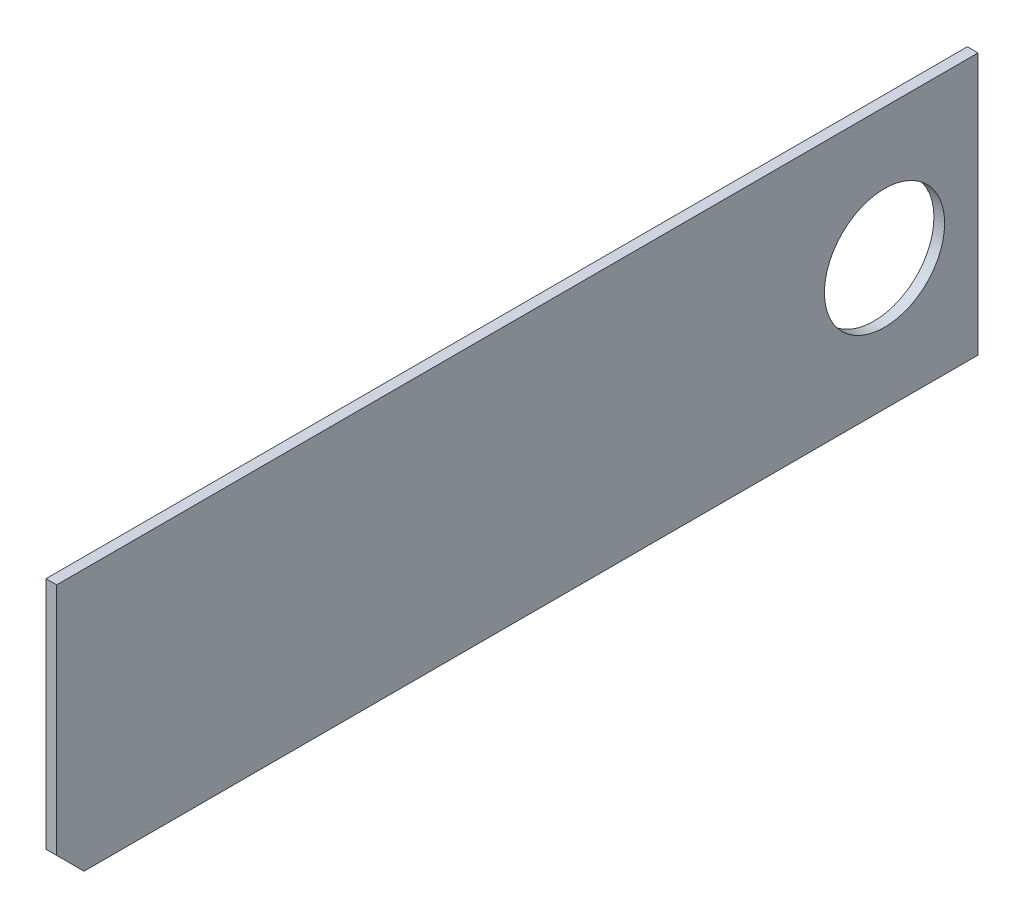
SolidWorks part; units mm, degrees
material "Q355"
ref_plane "前视基准面" through (0, 0, 0) normal (0, 0, 1) x (1, 0, 0)
ref_plane "上视基准面" through (0, 0, 0) normal (0, 1, 0) x (1, 0, 0)
ref_plane "右视基准面" through (0, 0, 0) normal (1, 0, 0) x (0, 0, -1)
sketch "草图1" plane through (0, 0, 0) normal (1, 0, 0) x (0, 0, -1)
  line L0 (70, 98) -> (-620, 98)
  line L1 (-620, 98) -> (-620, -77.5)
  line L2 (-620, -77.5) -> (-599.5, -98)
  line L3 (-599.5, -98) -> (70, -98)
  line L4 (70, 98) -> (70, -98)
  circle A0 centre (0, 0) radius 45
  dimension "D1" = 690
  dimension "D2" = 90
  dimension "D4" = 98
  dimension "D5" = 620
  dimension "D3" = 196
  dimension "D6" = 20.5
  dimension "D7" = 20.5
extrude "凸台-拉伸1" add sketch "草图1" along normal blind 8
